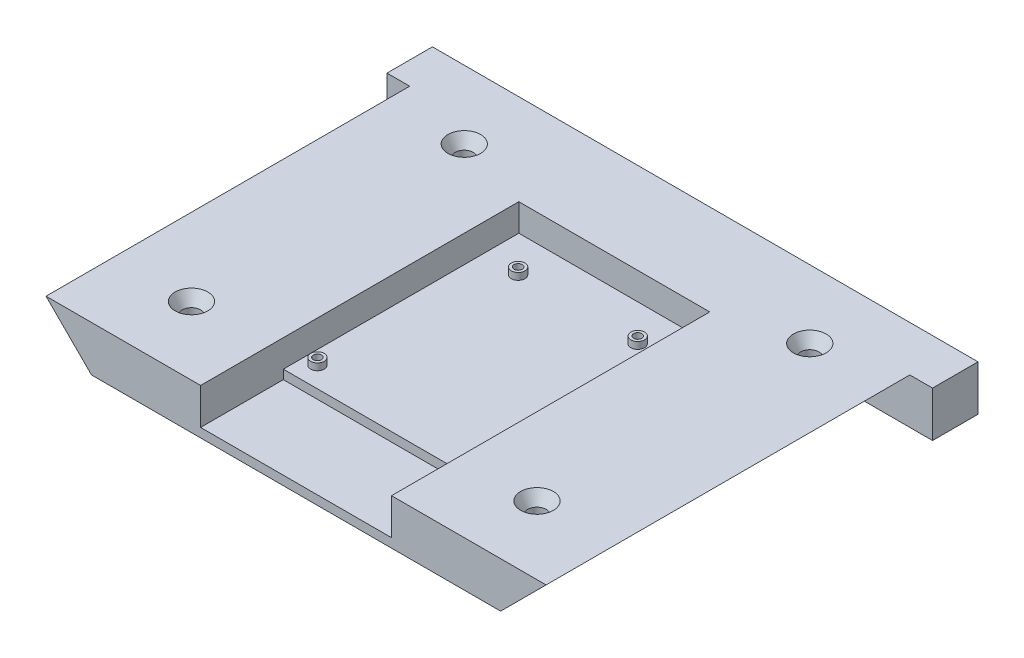
SolidWorks part; units mm, degrees
ref_plane "Front Plane" through (0, 0, 0) normal (0, 0, 1) x (1, 0, 0)
ref_plane "Top Plane" through (0, 0, 0) normal (0, 1, 0) x (1, 0, 0)
ref_plane "Right Plane" through (0, 0, 0) normal (1, 0, 0) x (0, 0, -1)
sketch "Sketch1" plane through (0, 0, 0) normal (0, 1, 0) x (1, 0, 0)
  line L0 (0, 0) -> (0, -45) construction
  line L1 (-60, -45) -> (60, -45) construction
  line L3 (-60, 45) -> (60, 45)
  line L4 (-60, 45) -> (-60, -45)
  line L5 (-60, -45) -> (60, -45)
  line L6 (60, 45) -> (60, -45)
  line L7 (-60, 45) -> (60, -45) construction
  line L8 (-60, -45) -> (60, 45) construction
  point P36 (0, -45)
extrude "body" add sketch "Sketch1" along normal blind 10
sketch "Sketch4" plane through (0, 0, 45) normal (0, 0, 1) x (1, 0, 0)
  line L0 (-60, 10) -> (-60, 0)
  line L1 (-60, 0) -> (-45, 0)
  line L2 (-60, 0) -> (60, 0) construction
  line L4 (-60, 10) -> (-55, 10)
  line L5 (-60, 10) -> (60, 10) construction
  line L6 (-55, 10) -> (-45, 0)
extrude "left cut" cut sketch "Sketch4" against normal offset from surface (80 mm away) 10 contours L1 L6 L4 L0 up to face at (0, 5, -45)
mirror "right cut(mirror)" about plane through (0, 0, 0) normal (1, 0, 0) of "left cut"
sketch "Sketch5" plane through (0, 10, 0) normal (0, 1, 0) x (1, 0, 0)
  line L0 (-55, -45) -> (55, -45) construction
  line L1 (-21, -45) -> (21, -45)
  line L2 (0, 45) -> (0, 25) construction
  line L3 (60, 45) -> (-60, 45) construction
  line L4 (-21, 25) -> (21, 25)
  line L5 (-21, 25) -> (-21, -45)
  line L6 (21, 25) -> (21, -45)
  point P5 (0, -45)
  point P12 (0, 25)
extrude "rfid room" cut sketch "Sketch5" against normal offset from surface (6 mm away) 4 up to face at (0, 0, -17.5)
sketch "Sketch12" plane through (0, 4, 0) normal (0, 1, 0) x (1, 0, 0)
  line L0 (0, 25) -> (0, 17) construction
  line L1 (21, 25) -> (-21, 25) construction
  line L2 (11.65, 17) -> (21, 17) construction
  line L3 (21, -45) -> (21, 25) construction
  line L4 (-11.65, 17) -> (-21, 17) construction
  line L5 (-21, 25) -> (-21, -45) construction
  line L6 (-21, 17) -> (-13.15, 17) construction
  line L7 (21, 17) -> (13.15, 17) construction
  line L8 (-21, 25) -> (-21, -22.3) construction
  line L9 (21, 25) -> (21, -22.3) construction
  line L10 (21, -45) -> (21, 25) construction
  line L11 (-21, -22.3) -> (-18, -22.3) construction
  line L12 (21, -22.3) -> (18, -22.3) construction
  circle A0 centre (-13.15, 17) radius 1.5
  circle A1 centre (13.15, 17) radius 1.5
  circle A2 centre (-18, -22.3) radius 1.5
  circle A3 centre (18, -22.3) radius 1.5
extrude "outer screw hole rfid" add sketch "Sketch12" along normal blind 1.5
sketch "Sketch14" plane through (0, 5.5, 0) normal (0, 1, 0) x (1, 0, 0)
  circle A2 centre (18, -22.3) radius 0.9
  circle A3 centre (-18, -22.3) radius 0.9
extrude "inner screw hole rfid" cut sketch "Sketch14" against normal blind 3
sketch "Sketch15" plane through (0, 4, 0) normal (0, 1, 0) x (1, 0, 0)
  line L0 (-18, -23.8) -> (-18, -26.8) construction
  line L1 (-18, -26.8) -> (-21, -26.8)
  line L2 (-21, 25) -> (-21, -45) construction
  line L3 (-18, -26.8) -> (21, -26.8)
  line L4 (21, -45) -> (21, 25) construction
  line L16 (21, -26.8) -> (21, -45)
  line L17 (-21, -26.8) -> (-21, -45)
  line L18 (21, -45) -> (-21, -45)
  circle A0 centre (-18, -22.3) radius 1.5 construction
  circle A1 centre (-18, -22.3) radius 1.5 construction
  point P0 (-18, -23.8)
extrude "rfid upper cut" cut sketch "Sketch15" against normal blind 2
sketch "Sketch17" plane through (0, 5.5, 0) normal (0, 1, 0) x (1, 0, 0)
  circle A0 centre (-13.15, 17) radius 0.9
  circle A1 centre (13.15, 17) radius 0.9
extrude "inner screw cut down" cut sketch "Sketch17" against normal blind 1.5
sketch "Sketch6" plane through (0, 10, 0) normal (0, 1, 0) x (1, 0, 0)
  line L0 (-55, -45) -> (-21, -45) construction
  line L1 (21, -45) -> (55, -45) construction
  line L2 (-38, -45) -> (-38, 45) construction
  line L3 (60, 45) -> (-60, 45) construction
  line L4 (38, -45) -> (38, 45) construction
  line L5 (-55, 35) -> (55, 35) construction
  circle A0 centre (-38, 30) radius 3.6
  circle A1 centre (38, 30) radius 3.6
  circle A2 centre (-38, -30) radius 3.6
  circle A3 centre (38, -30) radius 3.6
  point P0 (-38, -45)
  point P1 (38, -45)
  point P12 (-55, 35)
  point P13 (55, 35)
  point P18 (-38, 35)
  point P19 (38, 35)
  point P20 (-38, 30)
  point P21 (38, 30)
  point P22 (-38, -30)
  point P23 (38, -30)
extrude "outer hole up" cut sketch "Sketch6" against normal blind 2.6 draft 31.608
sketch "Sketch7" plane through (0, 7.4, 0) normal (0, 1, 0) x (1, 0, 0)
  circle A0 centre (-38, 30) radius 2
  circle A1 centre (-38, -30) radius 2
  circle A2 centre (38, 30) radius 2
  circle A3 centre (38, -30) radius 2
  point P0 (-38, 30)
  point P1 (-38, -30)
  point P3 (38, -30)
  point P5 (38, 30)
extrude "inner hole" cut sketch "Sketch7" against normal through all
sketch "Sketch11" plane through (0, 0, 0) normal (0, -1, 0) x (1, 0, 0)
  circle A0 centre (-38, 30) radius 3.6
  circle A1 centre (-38, -30) radius 3.6
  circle A2 centre (38, 30) radius 3.6
  circle A3 centre (38, -30) radius 3.6
  point P0 (-38, 30)
  point P1 (-38, -30)
  point P3 (38, -30)
  point P5 (38, 30)
extrude "outer hole down" cut sketch "Sketch11" against normal blind 2.6 draft 31.608
sketch "Sketch9" plane through (0, 0, 0) normal (0, 1, 0) x (-1, 0, 0)
  spline S0 degree 3 poles (-11.5085, 3.6845) (-11.45, 3.9173) (-11.327, 4.2475) (-11.2353, 4.4182) knots 0 0 0 0 1 1 1 1
  spline S1 degree 3 poles (-11.2353, 4.4182) (-11.1436, 4.5889) (-9.9757, 6.1446) (-8.6401, 7.8754) knots 1 1 1 1 2 2 2 2
  spline S2 degree 3 poles (-8.6401, 7.8754) (-7.3044, 9.6062) (-5.2308, 12.2922) (-4.032, 13.8445) knots 2 2 2 2 3 3 3 3
  spline S3 degree 3 poles (-4.032, 13.8445) (-2.8333, 15.3967) (-1.5136, 17.1844) (-1.0994, 17.8172) knots 3 3 3 3 4 4 4 4
  spline S4 degree 3 poles (-1.0994, 17.8172) (-0.6853, 18.45) (-0.3464, 19.0691) (-0.3464, 19.193) knots 4 4 4 4 5 5 5 5
  spline S5 degree 3 poles (-0.3464, 19.193) (-0.3464, 19.3788) (-0.5262, 19.4182) (-1.3695, 19.4172) knots 5 5 5 5 6 6 6 6
  spline S6 degree 3 poles (-1.3695, 19.4172) (-1.9321, 19.4167) (-3.1531, 19.2579) (-4.0827, 19.0645) knots 6 6 6 6 7 7 7 7
  spline S7 degree 3 poles (-4.0827, 19.0645) (-5.0123, 18.871) (-6.2146, 18.7128) (-6.7545, 18.7128) knots 7 7 7 7 8 8 8 8
  spline S8 degree 3 poles (-6.7545, 18.7128) (-7.4613, 18.7128) (-7.9065, 18.7952) (-8.3442, 19.0071) knots 8 8 8 8 9 9 9 9
  spline S9 degree 3 poles (-8.3442, 19.0071) (-8.6786, 19.169) (-9.0861, 19.4895) (-9.2497, 19.7193) knots 9 9 9 9 10 10 10 10
  spline S10 degree 3 poles (-9.2497, 19.7193) (-9.4134, 19.9491) (-9.5795, 20.3772) (-9.6188, 20.6706) knots 10 10 10 10 11 11 11 11
  spline S11 degree 3 poles (-9.6188, 20.6706) (-9.6688, 21.0434) (-9.6025, 21.3762) (-9.3987, 21.7757) knots 11 11 11 11 12 12 12 12
  spline S12 degree 3 poles (-9.3987, 21.7757) (-9.2383, 22.0901) (-8.8122, 22.6069) (-8.4517, 22.9242) knots 12 12 12 12 13 13 13 13
  spline S13 degree 3 poles (-8.4517, 22.9242) (-8.0912, 23.2415) (-7.4554, 23.6287) (-7.0387, 23.7846) knots 13 13 13 13 14 14 14 14
  spline S14 degree 3 poles (-7.0387, 23.7846) (-6.6221, 23.9405) (-5.6285, 24.2106) (-4.8307, 24.3848) knots 14 14 14 14 15 15 15 15
  spline S15 degree 3 poles (-4.8307, 24.3848) (-3.5695, 24.6602) (-2.9249, 24.8523) (-0.2254, 24.8498) knots 15 15 15 15 16 16 16 16
  spline S16 degree 3 poles (-0.2254, 24.8498) (2.4572, 24.8473) (3.0299, 24.6525) (4.3103, 24.3774) knots 16 16 16 16 17 17 17 17
  spline S17 degree 3 poles (4.3103, 24.3774) (5.1252, 24.2023) (6.141, 23.9002) (6.5676, 23.7061) knots 17 17 17 17 18 18 18 18
  spline S18 degree 3 poles (6.5676, 23.7061) (6.9943, 23.512) (7.4924, 23.2139) (7.6747, 23.0438) knots 18 18 18 18 19 19 19 19
  spline S19 degree 3 poles (7.6747, 23.0438) (7.8569, 22.8737) (8.0952, 22.563) (8.2042, 22.3534) knots 19 19 19 19 20 20 20 20
  spline S20 degree 3 poles (8.2042, 22.3534) (8.3133, 22.1438) (8.4025, 21.7876) (8.4025, 21.5617) knots 20 20 20 20 21 21 21 21
  spline S21 degree 3 poles (8.4025, 21.5617) (8.4025, 21.3359) (8.2395, 20.9109) (8.0404, 20.6174) knots 21 21 21 21 22 22 22 22
  spline S22 degree 3 poles (8.0404, 20.6174) (7.8412, 20.3239) (6.3619, 18.3942) (4.753, 16.3291) knots 22 22 22 22 23 23 23 23
  spline S23 degree 3 poles (4.753, 16.3291) (3.1441, 14.2641) (0.651, 11.0505) (-0.7872, 9.1878) knots 23 23 23 23 24 24 24 24
  spline S24 degree 3 poles (-0.7872, 9.1878) (-2.2254, 7.3251) (-3.5486, 5.5993) (-3.7277, 5.3527) knots 24 24 24 24 25 25 25 25
  spline S25 degree 3 poles (-3.7277, 5.3527) (-3.9068, 5.1061) (-4.0181, 4.8126) (-3.9751, 4.7006) knots 25 25 25 25 26 26 26 26
  spline S26 degree 3 poles (-3.9751, 4.7006) (-3.9283, 4.5784) (-3.5391, 4.436) (-3.0036, 4.3449) knots 26 26 26 26 27 27 27 27
  spline S27 degree 3 poles (-3.0036, 4.3449) (-2.5123, 4.2613) (-1.7508, 4.158) (-1.3115, 4.1153) knots 27 27 27 27 28 28 28 28
  spline S28 degree 3 poles (-1.3115, 4.1153) (-0.8721, 4.0727) (0.1315, 4.1038) (0.9188, 4.1846) knots 28 28 28 28 29 29 29 29
  spline S29 degree 3 poles (0.9188, 4.1846) (1.7061, 4.2654) (2.9341, 4.4839) (3.6477, 4.6701) knots 29 29 29 29 30 30 30 30
  spline S30 degree 3 poles (3.6477, 4.6701) (4.3614, 4.8563) (5.4215, 5.2058) (6.0034, 5.4467) knots 30 30 30 30 31 31 31 31
  spline S31 degree 3 poles (6.0034, 5.4467) (6.5854, 5.6875) (7.4744, 5.9537) (7.979, 6.0381) knots 31 31 31 31 32 32 32 32
  spline S32 degree 3 poles (7.979, 6.0381) (8.6659, 6.1531) (9.0499, 6.1494) (9.5075, 6.0232) knots 32 32 32 32 33 33 33 33
  spline S33 degree 3 poles (9.5075, 6.0232) (9.8435, 5.9305) (10.3438, 5.6482) (10.6192, 5.3958) knots 33 33 33 33 34 34 34 34
  spline S34 degree 3 poles (10.6192, 5.3958) (11.0383, 5.0118) (11.1314, 4.8178) (11.1901, 4.2065) knots 34 34 34 34 35 35 35 35
  spline S35 degree 3 poles (11.1901, 4.2065) (11.2313, 3.7781) (11.1871, 3.2993) (11.0833, 3.0487) knots 35 35 35 35 36 36 36 36
  spline S36 degree 3 poles (11.0833, 3.0487) (10.9859, 2.8137) (10.5611, 2.3059) (10.1393, 1.9203) knots 36 36 36 36 37 37 37 37
  spline S37 degree 3 poles (10.1393, 1.9203) (9.7174, 1.5348) (8.9143, 1.002) (8.3547, 0.7365) knots 37 37 37 37 38 38 38 38
  spline S38 degree 3 poles (8.3547, 0.7365) (7.795, 0.4709) (6.672, 0.032) (5.859, -0.2389) knots 38 38 38 38 39 39 39 39
  spline S39 degree 3 poles (5.859, -0.2389) (5.046, -0.5098) (3.8411, -0.8485) (3.1814, -0.9917) knots 39 39 39 39 40 40 40 40
  spline S40 degree 3 poles (3.1814, -0.9917) (2.2457, -1.1947) (1.3769, -1.4031) (-0.7697, -1.4031) knots 40 40 40 40 41 41 41 41
  spline S41 degree 3 poles (-0.7697, -1.4031) (-2.9188, -1.4031) (-3.7841, -1.1948) (-4.7208, -0.9912) knots 41 41 41 41 42 42 42 42
  spline S42 degree 3 poles (-4.7208, -0.9912) (-5.3805, -0.8478) (-6.4207, -0.5731) (-7.0323, -0.3808) knots 42 42 42 42 43 43 43 43
  spline S43 degree 3 poles (-7.0323, -0.3808) (-7.6439, -0.1884) (-8.6277, 0.1892) (-9.2185, 0.4585) knots 43 43 43 43 44 44 44 44
  spline S44 degree 3 poles (-9.2185, 0.4585) (-9.8093, 0.7277) (-10.4422, 1.0874) (-10.625, 1.2579) knots 44 44 44 44 45 45 45 45
  spline S45 degree 3 poles (-10.625, 1.2579) (-10.8078, 1.4283) (-11.0726, 1.7287) (-11.2136, 1.9253) knots 45 45 45 45 46 46 46 46
  spline S46 degree 3 poles (-11.2136, 1.9253) (-11.3546, 2.122) (-11.5026, 2.503) (-11.5425, 2.772) knots 46 46 46 46 47 47 47 47
  spline S47 degree 3 poles (-11.5425, 2.772) (-11.5824, 3.041) (-11.5671, 3.4516) (-11.5085, 3.6845) knots 47 47 47 47 48 48 48 48
  spline S48 degree 3 poles (-16.5702, -5.8963) (-16.4962, -5.6554) (-16.1258, -5.1684) (-15.747, -4.8141) knots 0 0 0 0 1 1 1 1
  spline S49 degree 3 poles (-15.747, -4.8141) (-15.2028, -4.305) (-14.9167, -4.1487) (-14.3825, -4.0686) knots 1 1 1 1 2 2 2 2
  spline S50 degree 3 poles (-14.3825, -4.0686) (-13.8014, -3.9815) (-13.5562, -4.0314) (-12.6356, -4.4244) knots 2 2 2 2 3 3 3 3
  spline S51 degree 3 poles (-12.6356, -4.4244) (-12.0467, -4.6758) (-10.7678, -5.1578) (-9.7936, -5.4956) knots 3 3 3 3 4 4 4 4
  spline S52 degree 3 poles (-9.7936, -5.4956) (-8.8195, -5.8334) (-7.232, -6.2695) (-6.2659, -6.4648) knots 4 4 4 4 5 5 5 5
  spline S53 degree 3 poles (-6.2659, -6.4648) (-5.2997, -6.66) (-3.599, -6.891) (-2.4866, -6.978) knots 5 5 5 5 6 6 6 6
  spline S54 degree 3 poles (-2.4866, -6.978) (-0.989, -7.0952) (0.0365, -7.095) (1.4645, -6.9772) knots 6 6 6 6 7 7 7 7
  spline S55 degree 3 poles (1.4645, -6.9772) (2.5252, -6.8897) (4.1719, -6.6611) (5.124, -6.4691) knots 7 7 7 7 8 8 8 8
  spline S56 degree 3 poles (5.124, -6.4691) (6.076, -6.2772) (7.4713, -5.9228) (8.2246, -5.6815) knots 8 8 8 8 9 9 9 9
  spline S57 degree 3 poles (8.2246, -5.6815) (8.9779, -5.4402) (10.1502, -5.0016) (10.8297, -4.7069) knots 9 9 9 9 10 10 10 10
  spline S58 degree 3 poles (10.8297, -4.7069) (11.5092, -4.4121) (12.2635, -4.1274) (12.5059, -4.0742) knots 10 10 10 10 11 11 11 11
  spline S59 degree 3 poles (12.5059, -4.0742) (12.7485, -4.0209) (13.2266, -4.0558) (13.5697, -4.1519) knots 11 11 11 11 12 12 12 12
  spline S60 degree 3 poles (13.5697, -4.1519) (13.9511, -4.2587) (14.4077, -4.5412) (14.7467, -4.8802) knots 12 12 12 12 13 13 13 13
  spline S61 degree 3 poles (14.7467, -4.8802) (15.0514, -5.1849) (15.3752, -5.6601) (15.4664, -5.9363) knots 13 13 13 13 14 14 14 14
  spline S62 degree 3 poles (15.4664, -5.9363) (15.5575, -6.2125) (15.5999, -6.7239) (15.5606, -7.0727) knots 14 14 14 14 15 15 15 15
  spline S63 degree 3 poles (15.5606, -7.0727) (15.5178, -7.4524) (15.3251, -7.9411) (15.0804, -8.2906) knots 15 15 15 15 16 16 16 16
  spline S64 degree 3 poles (15.0804, -8.2906) (14.7954, -8.6978) (14.3924, -9.0133) (13.7486, -9.3334) knots 16 16 16 16 17 17 17 17
  spline S65 degree 3 poles (13.7486, -9.3334) (13.2409, -9.5859) (12.1453, -10.0487) (11.314, -10.362) knots 17 17 17 17 18 18 18 18
  spline S66 degree 3 poles (11.314, -10.362) (10.4828, -10.6752) (8.9637, -11.1459) (7.9384, -11.4078) knots 18 18 18 18 19 19 19 19
  spline S67 degree 3 poles (7.9384, -11.4078) (6.913, -11.6698) (5.3439, -11.9993) (4.4514, -12.1401) knots 19 19 19 19 20 20 20 20
  spline S68 degree 3 poles (4.4514, -12.1401) (3.2, -12.3375) (2.3901, -12.5967) (-0.2759, -12.5934) knots 20 20 20 20 21 21 21 21
  spline S69 degree 3 poles (-0.2759, -12.5934) (-3.2237, -12.5897) (-4.3652, -12.3397) (-5.9823, -12.0634) knots 21 21 21 21 22 22 22 22
  spline S70 degree 3 poles (-5.9823, -12.0634) (-7.0253, -11.8852) (-8.6446, -11.529) (-9.5806, -11.2717) knots 22 22 22 22 23 23 23 23
  spline S71 degree 3 poles (-9.5806, -11.2717) (-10.5167, -11.0145) (-11.9493, -10.5441) (-12.7642, -10.2264) knots 23 23 23 23 24 24 24 24
  spline S72 degree 3 poles (-12.7642, -10.2264) (-13.5791, -9.9087) (-14.5929, -9.4734) (-15.0171, -9.259) knots 24 24 24 24 25 25 25 25
  spline S73 degree 3 poles (-15.0171, -9.259) (-15.5085, -9.0106) (-15.9381, -8.6561) (-16.201, -8.282) knots 25 25 25 25 26 26 26 26
  spline S74 degree 3 poles (-16.201, -8.282) (-16.4875, -7.8744) (-16.6276, -7.4868) (-16.6592, -7.0146) knots 26 26 26 26 27 27 27 27
  spline S75 degree 3 poles (-16.6592, -7.0146) (-16.6842, -6.6405) (-16.6442, -6.1373) (-16.5702, -5.8963) knots 27 27 27 27 28 28 28 28
  spline S76 degree 3 poles (-20.3741, -14.7593) (-20.2047, -14.4258) (-19.8677, -14.0031) (-19.6254, -13.8198) knots 0 0 0 0 1 1 1 1
  spline S77 degree 3 poles (-19.6254, -13.8198) (-19.383, -13.6365) (-18.9173, -13.4154) (-18.5903, -13.3284) knots 1 1 1 1 2 2 2 2
  spline S78 degree 3 poles (-18.5903, -13.3284) (-18.2634, -13.2414) (-17.8189, -13.2127) (-17.6025, -13.2644) knots 2 2 2 2 3 3 3 3
  spline S79 degree 3 poles (-17.6025, -13.2644) (-17.3862, -13.3162) (-16.5702, -13.6292) (-15.7892, -13.96) knots 3 3 3 3 4 4 4 4
  spline S80 degree 3 poles (-15.7892, -13.96) (-15.0083, -14.2908) (-13.472, -14.8504) (-12.3752, -15.2035) knots 4 4 4 4 5 5 5 5
  spline S81 degree 3 poles (-12.3752, -15.2035) (-11.2785, -15.5567) (-9.6209, -16.0062) (-8.6917, -16.2023) knots 5 5 5 5 6 6 6 6
  spline S82 degree 3 poles (-8.6917, -16.2023) (-7.7625, -16.3985) (-6.1873, -16.6626) (-5.1913, -16.7893) knots 6 6 6 6 7 7 7 7
  spline S83 degree 3 poles (-5.1913, -16.7893) (-4.052, -16.9341) (-2.3336, -17.0195) (-0.5581, -17.0195) knots 7 7 7 7 8 8 8 8
  spline S84 degree 3 poles (-0.5581, -17.0195) (1.1976, -17.0195) (2.9363, -16.934) (4.0429, -16.7932) knots 8 8 8 8 9 9 9 9
  spline S85 degree 3 poles (4.0429, -16.7932) (5.0212, -16.6688) (6.4499, -16.4392) (7.2179, -16.2829) knots 9 9 9 9 10 10 10 10
  spline S86 degree 3 poles (7.2179, -16.2829) (7.9858, -16.1267) (9.3126, -15.8032) (10.1664, -15.564) knots 10 10 10 10 11 11 11 11
  spline S87 degree 3 poles (10.1664, -15.564) (11.0201, -15.3249) (12.7663, -14.7079) (14.0469, -14.193) knots 11 11 11 11 12 12 12 12
  spline S88 degree 3 poles (14.0469, -14.193) (15.7717, -13.4994) (16.5431, -13.2582) (17.023, -13.2626) knots 12 12 12 12 13 13 13 13
  spline S89 degree 3 poles (17.023, -13.2626) (17.4422, -13.2664) (17.8539, -13.3818) (18.1902, -13.5896) knots 13 13 13 13 14 14 14 14
  spline S90 degree 3 poles (18.1902, -13.5896) (18.4759, -13.7661) (18.878, -14.1314) (19.0839, -14.4013) knots 14 14 14 14 15 15 15 15
  spline S91 degree 3 poles (19.0839, -14.4013) (19.3484, -14.7481) (19.4766, -15.1147) (19.5211, -15.6514) knots 15 15 15 15 16 16 16 16
  spline S92 degree 3 poles (19.5211, -15.6514) (19.5558, -16.0691) (19.5431, -16.5741) (19.493, -16.7737) knots 16 16 16 16 17 17 17 17
  spline S93 degree 3 poles (19.493, -16.7737) (19.443, -16.9732) (19.1793, -17.383) (18.9071, -17.6843) knots 17 17 17 17 18 18 18 18
  spline S94 degree 3 poles (18.9071, -17.6843) (18.5483, -18.0815) (18.0041, -18.4108) (16.9275, -18.8823) knots 18 18 18 18 19 19 19 19
  spline S95 degree 3 poles (16.9275, -18.8823) (16.1108, -19.24) (14.7197, -19.7818) (13.8362, -20.0865) knots 19 19 19 19 20 20 20 20
  spline S96 degree 3 poles (13.8362, -20.0865) (12.9526, -20.3912) (11.3527, -20.8606) (10.2808, -21.1296) knots 20 20 20 20 21 21 21 21
  spline S97 degree 3 poles (10.2808, -21.1296) (9.2089, -21.3986) (7.5382, -21.75) (6.568, -21.9105) knots 21 21 21 21 22 22 22 22
  spline S98 degree 3 poles (6.568, -21.9105) (5.5979, -22.071) (4.0421, -22.2668) (3.1108, -22.3455) knots 22 22 22 22 23 23 23 23
  spline S99 degree 3 poles (3.1108, -22.3455) (2.1795, -22.4243) (0.5285, -22.4887) (-0.5581, -22.4887) knots 23 23 23 23 24 24 24 24
  spline S100 degree 3 poles (-0.5581, -22.4887) (-1.6446, -22.4887) (-3.2956, -22.4243) (-4.227, -22.3455) knots 24 24 24 24 25 25 25 25
  spline S101 degree 3 poles (-4.227, -22.3455) (-5.1583, -22.2668) (-6.7141, -22.0715) (-7.6842, -21.9117) knots 25 25 25 25 26 26 26 26
  spline S102 degree 3 poles (-7.6842, -21.9117) (-8.6543, -21.7519) (-10.4006, -21.3788) (-11.5647, -21.0826) knots 26 26 26 26 27 27 27 27
  spline S103 degree 3 poles (-11.5647, -21.0826) (-12.7289, -20.7865) (-14.5069, -20.2455) (-15.5159, -19.8804) knots 27 27 27 27 28 28 28 28
  spline S104 degree 3 poles (-15.5159, -19.8804) (-16.5248, -19.5154) (-17.8885, -18.9535) (-18.5463, -18.6317) knots 28 28 28 28 29 29 29 29
  spline S105 degree 3 poles (-18.5463, -18.6317) (-19.3553, -18.236) (-19.8776, -17.8747) (-20.1603, -17.5153) knots 29 29 29 29 30 30 30 30
  spline S106 degree 3 poles (-20.1603, -17.5153) (-20.4883, -17.0983) (-20.5893, -16.8099) (-20.6302, -16.1748) knots 30 30 30 30 31 31 31 31
  spline S107 degree 3 poles (-20.6302, -16.1748) (-20.6704, -15.549) (-20.6123, -15.2281) (-20.3741, -14.7593) knots 31 31 31 31 32 32 32 32
extrude "logo" cut sketch "Sketch9" along normal blind 2
equation "\"D3@outer hole up\"=atn( 1.6/2.6)"
equation "\"D3@outer hole down\"=atn( 1.6/2.6)"
